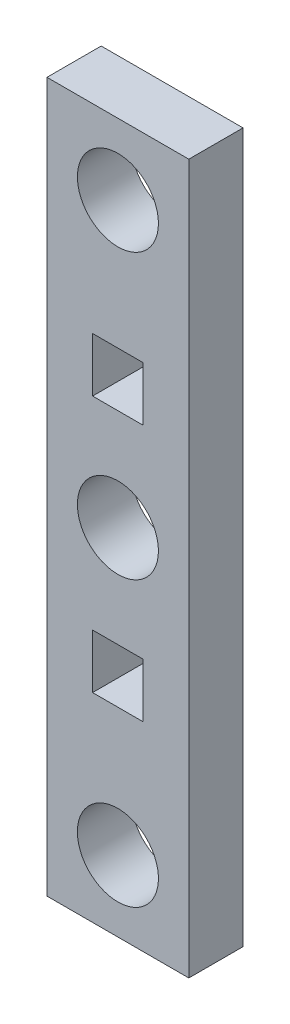
SolidWorks part; units mm, degrees
ref_plane "Front Plane" through (0, 0, 0) normal (0, 0, 1) x (1, 0, 0)
ref_plane "Top Plane" through (0, 0, 0) normal (0, 1, 0) x (1, 0, 0)
ref_plane "Right Plane" through (0, 0, 0) normal (1, 0, 0) x (0, 0, -1)
sketch "Model" plane through (0, 0, 0) normal (0, 0, 1) x (1, 0, 0)
  line L0 (7, 70) -> (7, 0) construction
  line L1 (0, 0) -> (14, 0)
  line L2 (0, 0) -> (0, 70)
  line L3 (0, 70) -> (14, 70)
  line L4 (14, 0) -> (14, 70)
  line L5 (0, 35) -> (14, 35) construction
  line L6 (4.5, 19.65) -> (9.5, 25) construction
  line L7 (4.5, 45) -> (9.5, 45)
  line L8 (4.5, 45) -> (4.5, 50.35)
  line L9 (4.5, 50.35) -> (9.5, 50.35)
  line L10 (9.5, 45) -> (9.5, 50.35)
  line L11 (4.5, 45) -> (9.5, 50.35) construction
  line L12 (4.5, 50.35) -> (9.5, 45) construction
  line L13 (4.5, 25) -> (9.5, 19.65) construction
  line L14 (9.5, 25) -> (9.5, 19.65)
  line L15 (4.5, 19.65) -> (9.5, 19.65)
  line L16 (4.5, 25) -> (4.5, 19.65)
  line L17 (4.5, 25) -> (9.5, 25)
  circle A0 centre (7, 63) radius 4
  circle A1 centre (7, 7) radius 4
  circle A2 centre (7, 35) radius 4
  point P10 (7, 47.675)
  point P21 (7, 22.325)
  dimension "D15" = 8
  dimension "D2" = 70
  dimension "D4" = 14
  dimension "D8" = 7
  dimension "D9" = 5.35
  dimension "D10" = 5
  dimension "D11" = 19.65
extrude "Boss-Extrude1" add sketch "Model" along normal blind 5.35
equation "\"mdfthick\"=5.35"
equation "\"D9@Model\"=\"mdfthick\""
equation "\"D1@Boss-Extrude1\"=\"mdfthick\""
